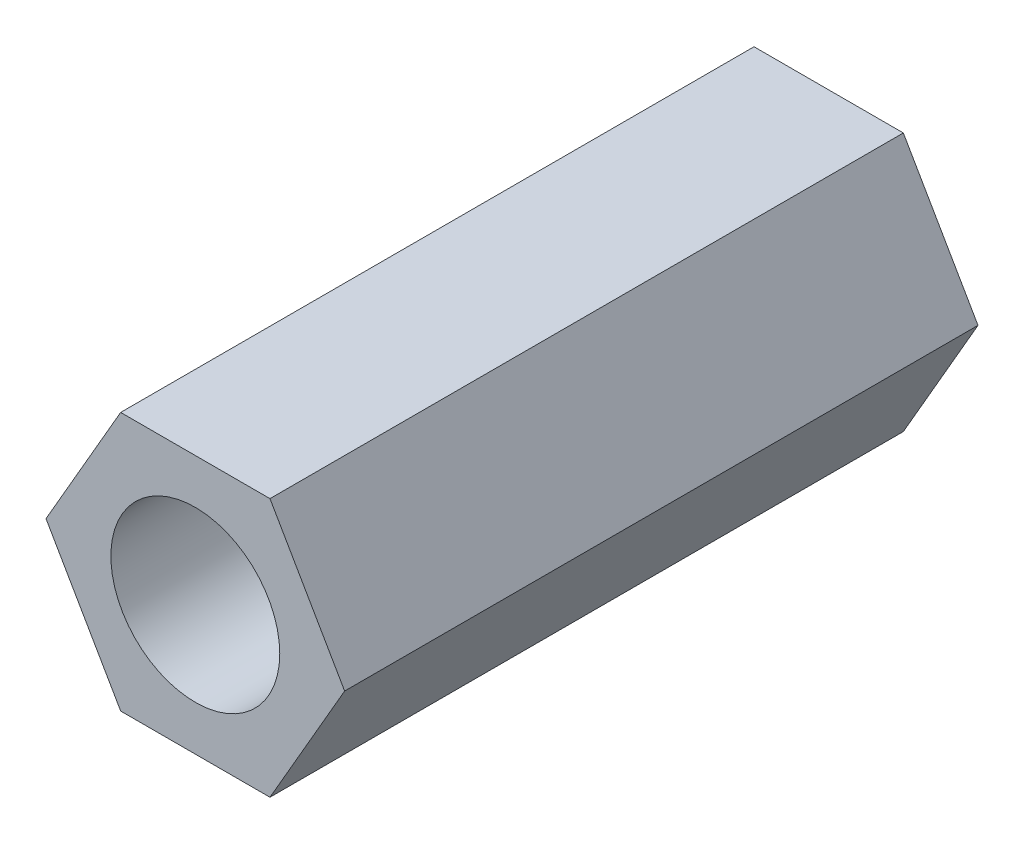
SolidWorks part; units mm, degrees
material "黄铜"
ref_plane "前视基准面" through (0, 0, 0) normal (0, 0, 1) x (1, 0, 0)
ref_plane "上视基准面" through (0, 0, 0) normal (0, 1, 0) x (1, 0, 0)
ref_plane "右视基准面" through (0, 0, 0) normal (1, 0, 0) x (0, 0, -1)
sketch "草图1" plane through (0, 0, 0) normal (0, 0, 1) x (1, 0, 0)
  line L1 (2.829, 0) -> (1.4145, 2.45)
  line L2 (1.4145, 2.45) -> (-1.4145, 2.45)
  line L3 (-1.4145, 2.45) -> (-2.829, 0)
  line L4 (-2.829, 0) -> (-1.4145, -2.45)
  line L5 (-1.4145, -2.45) -> (1.4145, -2.45)
  line L6 (1.4145, -2.45) -> (2.829, 0)
  circle A0 centre (0, 0) radius 1.6
  circle A1 centre (0, 0) radius 2.45 construction
  dimension "D1" = 3.2
  dimension "D2" = 4.9
extrude "凸台-拉伸1" add sketch "草图1" along normal blind 12
